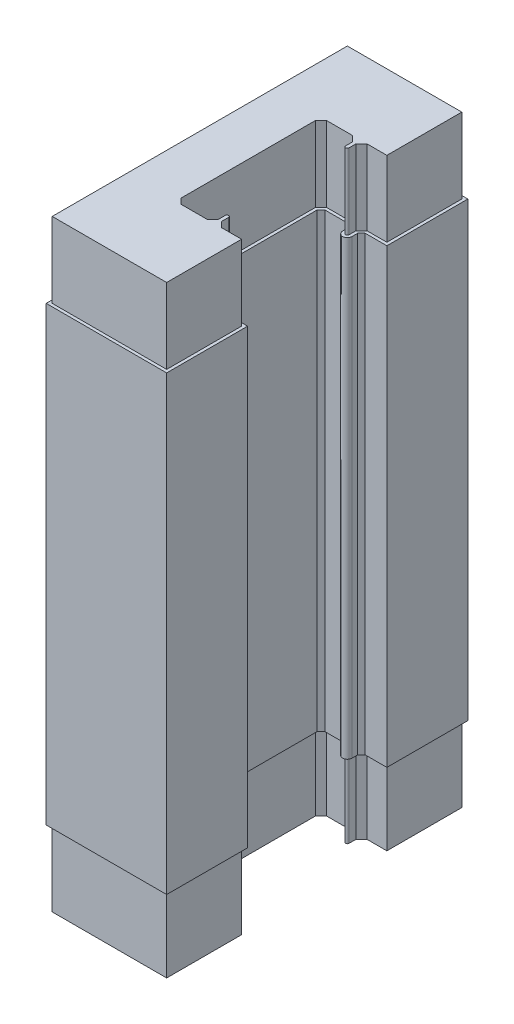
SolidWorks part; units mm, degrees
ref_plane "Front Plane" through (0, 0, 0) normal (0, 0, 1) x (1, 0, 0)
ref_plane "Top Plane" through (0, 0, 0) normal (0, 1, 0) x (1, 0, 0)
ref_plane "Right Plane" through (0, 0, 0) normal (1, 0, 0) x (0, 0, -1)
sketch "Sketch1" plane through (0, 0, 0) normal (0, 1, 0) x (1, 0, 0)
  line L1 (4.1023, -10.9252) -> (4.1023, 9.0748)
  line L4 (4.1023, -5.5502) -> (2.6648, -5.5502)
  line L6 (2.6648, -5.5502) -> (2.4148, -5.3002)
  line L7 (2.4148, -5.3002) -> (2.4148, -4.9252)
  line L8 (1.7898, -4.9252) -> (1.7898, -5.3002)
  line L9 (1.7898, -5.3002) -> (1.5398, -5.5502)
  line L10 (1.5398, -5.5502) -> (-0.0227, -5.5502)
  line L11 (-0.0227, -5.5502) -> (-0.2727, -5.3002)
  line L12 (-0.2727, -5.3002) -> (-0.2727, 3.4498)
  line L13 (2.6648, -5.5502) -> (2.4148, -5.3002)
  line L15 (-0.0227, 3.6998) -> (-0.2727, 3.4498)
  line L16 (1.5398, 3.6998) -> (-0.0227, 3.6998)
  line L17 (1.7898, 3.4498) -> (1.5398, 3.6998)
  line L18 (1.7898, 3.0748) -> (1.7898, 3.4498)
  line L19 (2.4148, 3.4498) -> (2.4148, 3.0748)
  line L20 (2.6648, 3.6998) -> (2.4148, 3.4498)
  line L21 (4.1023, 3.6998) -> (2.6648, 3.6998)
  line L22 (2.4148, -5.3002) -> (2.4148, -4.9252)
  line L23 (1.7898, -4.9252) -> (1.7898, -5.3002)
  line L24 (1.7898, -5.3002) -> (1.5398, -5.5502)
  line L25 (1.5398, -5.5502) -> (-0.0227, -5.5502)
  line L26 (-0.0227, -5.5502) -> (-0.2727, -5.3002)
  line L27 (-0.0227, 3.6998) -> (-0.2727, 3.4498)
  line L28 (1.5398, 3.6998) -> (-0.0227, 3.6998)
  line L29 (1.7898, 3.4498) -> (1.5398, 3.6998)
  line L30 (1.7898, 3.0748) -> (1.7898, 3.4498)
  line L31 (2.4148, 3.4498) -> (2.4148, 3.0748)
  line L32 (2.6648, 3.6998) -> (2.4148, 3.4498)
  line L34 (4.1023, 9.0748) -> (-3.8977, 9.0748)
  line L35 (-3.8977, 9.0748) -> (-3.8977, -10.9252)
  line L36 (-3.8977, -10.9252) -> (4.1023, -10.9252)
  line L38 (3.3835, 3.6998) -> (3.3835, -5.5502)
  arc A0 (2.4148, -4.9252) -> (2.1023, -4.6127) centre (2.1023, -4.9252) ccw
  arc A1 (2.1023, -4.6127) -> (1.7898, -4.9252) centre (2.1023, -4.9252) ccw
  arc A2 (2.1023, 2.7623) -> (1.7898, 3.0748) centre (2.1023, 3.0748) cw
  arc A3 (2.4148, 3.0748) -> (2.1023, 2.7623) centre (2.1023, 3.0748) cw
  arc A4 (2.4148, -4.9252) -> (2.1023, -4.6127) centre (2.1023, -4.9252) ccw
  arc A5 (2.1023, -4.6127) -> (1.7898, -4.9252) centre (2.1023, -4.9252) ccw
  arc A6 (2.1023, 2.7623) -> (1.7898, 3.0748) centre (2.1023, 3.0748) cw
  arc A7 (2.4148, 3.0748) -> (2.1023, 2.7623) centre (2.1023, 3.0748) cw
  point P20 (4.1023, -0.9252)
extrude "Boss-Extrude1" add sketch "Sketch1" along normal blind 40
sketch "Sketch8" plane through (0, 40, 0) normal (0, 1, 0) x (1, 0, 0)
  line L0 (2.3148, 3.0748) -> (2.3148, 3.4913)
  line L1 (2.3148, 3.4913) -> (2.6233, 3.7998)
  line L2 (2.6233, 3.7998) -> (4.0023, 3.7998)
  line L3 (4.0023, 3.7998) -> (4.0023, 8.9748)
  line L4 (4.0023, 8.9748) -> (-3.7977, 8.9748)
  line L5 (-3.7977, 8.9748) -> (-3.7977, -10.8252)
  line L6 (-3.7977, -10.8252) -> (4.0023, -10.8252)
  line L7 (4.0023, -10.8252) -> (4.0023, -5.6502)
  line L8 (4.0023, -5.6502) -> (2.6233, -5.6502)
  line L9 (2.6233, -5.6502) -> (2.3148, -5.3416)
  line L10 (2.3148, -5.3416) -> (2.3148, -4.9252)
  line L11 (1.8898, -4.9252) -> (1.8898, -5.3416)
  line L12 (1.8898, -5.3416) -> (1.5812, -5.6502)
  line L13 (1.5812, -5.6502) -> (-0.0642, -5.6502)
  line L14 (-0.0642, -5.6502) -> (-0.3727, -5.3416)
  line L15 (-0.3727, -5.3416) -> (-0.3727, 3.4913)
  line L16 (-0.3727, 3.4913) -> (-0.0642, 3.7998)
  line L17 (-0.0642, 3.7998) -> (1.5812, 3.7998)
  line L18 (1.5812, 3.7998) -> (1.8898, 3.4913)
  line L19 (1.8898, 3.4913) -> (1.8898, 3.0748)
  line L20 (2.4148, 3.0748) -> (2.4148, 3.4498)
  line L21 (2.4148, 3.4498) -> (2.6648, 3.6998)
  line L22 (2.6648, 3.6998) -> (4.1023, 3.6998)
  line L23 (4.1023, 3.6998) -> (4.1023, 9.0748)
  line L24 (4.1023, 9.0748) -> (-3.8977, 9.0748)
  line L25 (-3.8977, 9.0748) -> (-3.8977, -10.9252)
  line L26 (-3.8977, -10.9252) -> (4.1023, -10.9252)
  line L27 (4.1023, -10.9252) -> (4.1023, -5.5502)
  line L28 (4.1023, -5.5502) -> (2.6648, -5.5502)
  line L29 (2.6648, -5.5502) -> (2.4148, -5.3002)
  line L30 (2.4148, -5.3002) -> (2.4148, -4.9252)
  line L31 (1.7898, -4.9252) -> (1.7898, -5.3002)
  line L32 (1.7898, -5.3002) -> (1.5398, -5.5502)
  line L33 (1.5398, -5.5502) -> (-0.0227, -5.5502)
  line L34 (-0.0227, -5.5502) -> (-0.2727, -5.3002)
  line L35 (-0.2727, -5.3002) -> (-0.2727, 3.4498)
  line L36 (-0.2727, 3.4498) -> (-0.0227, 3.6998)
  line L37 (-0.0227, 3.6998) -> (1.5398, 3.6998)
  line L38 (1.5398, 3.6998) -> (1.7898, 3.4498)
  line L39 (1.7898, 3.4498) -> (1.7898, 3.0748)
  line L40 (2.4148, 3.0748) -> (2.4148, 3.4498)
  line L41 (2.4148, 3.4498) -> (2.6648, 3.6998)
  line L42 (2.6648, 3.6998) -> (4.1023, 3.6998)
  line L43 (4.1023, 3.6998) -> (4.1023, 9.0748)
  line L44 (4.1023, 9.0748) -> (-3.8977, 9.0748)
  line L45 (-3.8977, 9.0748) -> (-3.8977, -10.9252)
  line L46 (-3.8977, -10.9252) -> (4.1023, -10.9252)
  line L47 (4.1023, -10.9252) -> (4.1023, -5.5502)
  line L48 (4.1023, -5.5502) -> (2.6648, -5.5502)
  line L49 (2.6648, -5.5502) -> (2.4148, -5.3002)
  line L50 (2.4148, -5.3002) -> (2.4148, -4.9252)
  line L51 (1.7898, -4.9252) -> (1.7898, -5.3002)
  line L52 (1.7898, -5.3002) -> (1.5398, -5.5502)
  line L53 (1.5398, -5.5502) -> (-0.0227, -5.5502)
  line L54 (-0.0227, -5.5502) -> (-0.2727, -5.3002)
  line L55 (-0.2727, -5.3002) -> (-0.2727, 3.4498)
  line L56 (-0.2727, 3.4498) -> (-0.0227, 3.6998)
  line L57 (-0.0227, 3.6998) -> (1.5398, 3.6998)
  line L58 (1.5398, 3.6998) -> (1.7898, 3.4498)
  line L59 (1.7898, 3.4498) -> (1.7898, 3.0748)
  arc A0 (2.3148, -4.9252) -> (1.8898, -4.9252) centre (2.1023, -4.9252) ccw
  arc A1 (1.8898, 3.0748) -> (2.3148, 3.0748) centre (2.1023, 3.0748) ccw
  arc A2 (1.7898, 3.0748) -> (2.4148, 3.0748) centre (2.1023, 3.0748) ccw
  arc A3 (2.4148, -4.9252) -> (1.7898, -4.9252) centre (2.1023, -4.9252) ccw
  arc A4 (1.7898, 3.0748) -> (2.4148, 3.0748) centre (2.1023, 3.0748) ccw
  arc A5 (2.4148, -4.9252) -> (1.7898, -4.9252) centre (2.1023, -4.9252) ccw
  dimension "D1" = 0
  dimension "D2" = 0.1
extrude "Cut-Extrude6" cut sketch "Sketch8" against normal blind 5
sketch "Sketch9" plane through (0, 0, 0) normal (0, -1, 0) x (1, 0, 0)
  line L20 (1.7898, -3.0748) -> (1.7898, -3.4498)
  line L21 (1.7898, -3.4498) -> (1.5398, -3.6998)
  line L22 (1.5398, -3.6998) -> (-0.0227, -3.6998)
  line L23 (-0.0227, -3.6998) -> (-0.2727, -3.4498)
  line L24 (-0.2727, -3.4498) -> (-0.2727, 5.3002)
  line L25 (-0.2727, 5.3002) -> (-0.0227, 5.5502)
  line L26 (-0.0227, 5.5502) -> (1.5398, 5.5502)
  line L27 (1.5398, 5.5502) -> (1.7898, 5.3002)
  line L28 (1.7898, 5.3002) -> (1.7898, 4.9252)
  line L29 (2.4148, 4.9252) -> (2.4148, 5.3002)
  line L30 (2.4148, 5.3002) -> (2.6648, 5.5502)
  line L31 (2.6648, 5.5502) -> (4.1023, 5.5502)
  line L32 (4.1023, 5.5502) -> (4.1023, 10.9252)
  line L33 (4.1023, 10.9252) -> (-3.8977, 10.9252)
  line L34 (-3.8977, 10.9252) -> (-3.8977, -9.0748)
  line L35 (-3.8977, -9.0748) -> (4.1023, -9.0748)
  line L36 (4.1023, -9.0748) -> (4.1023, -3.6998)
  line L37 (4.1023, -3.6998) -> (2.6648, -3.6998)
  line L38 (2.6648, -3.6998) -> (2.4148, -3.4498)
  line L39 (2.4148, -3.4498) -> (2.4148, -3.0748)
  line L40 (1.7898, -3.0748) -> (1.7898, -3.4498)
  line L41 (1.7898, -3.4498) -> (1.5398, -3.6998)
  line L42 (1.5398, -3.6998) -> (-0.0227, -3.6998)
  line L43 (-0.0227, -3.6998) -> (-0.2727, -3.4498)
  line L44 (-0.2727, -3.4498) -> (-0.2727, 5.3002)
  line L45 (-0.2727, 5.3002) -> (-0.0227, 5.5502)
  line L46 (-0.0227, 5.5502) -> (1.5398, 5.5502)
  line L47 (1.5398, 5.5502) -> (1.7898, 5.3002)
  line L48 (1.7898, 5.3002) -> (1.7898, 4.9252)
  line L49 (2.4148, 4.9252) -> (2.4148, 5.3002)
  line L50 (2.4148, 5.3002) -> (2.6648, 5.5502)
  line L51 (2.6648, 5.5502) -> (4.1023, 5.5502)
  line L52 (4.1023, 5.5502) -> (4.1023, 10.9252)
  line L53 (4.1023, 10.9252) -> (-3.8977, 10.9252)
  line L54 (-3.8977, 10.9252) -> (-3.8977, -9.0748)
  line L55 (-3.8977, -9.0748) -> (4.1023, -9.0748)
  line L56 (4.1023, -9.0748) -> (4.1023, -3.6998)
  line L57 (4.1023, -3.6998) -> (2.6648, -3.6998)
  line L58 (2.6648, -3.6998) -> (2.4148, -3.4498)
  line L59 (2.4148, -3.4498) -> (2.4148, -3.0748)
  line L60 (1.8898, -3.0748) -> (1.8898, -3.4913)
  line L61 (2.3148, -3.4913) -> (2.3148, -3.0748)
  line L62 (2.6233, -3.7998) -> (2.3148, -3.4913)
  line L63 (4.0023, -3.7998) -> (2.6233, -3.7998)
  line L64 (4.0023, -8.9748) -> (4.0023, -3.7998)
  line L65 (-3.7977, -8.9748) -> (4.0023, -8.9748)
  line L66 (-3.7977, 10.8252) -> (-3.7977, -8.9748)
  line L67 (4.0023, 10.8252) -> (-3.7977, 10.8252)
  line L68 (4.0023, 5.6502) -> (4.0023, 10.8252)
  line L69 (2.6233, 5.6502) -> (4.0023, 5.6502)
  line L70 (2.3148, 5.3416) -> (2.6233, 5.6502)
  line L71 (2.3148, 4.9252) -> (2.3148, 5.3416)
  line L72 (1.8898, 5.3416) -> (1.8898, 4.9252)
  line L73 (1.5812, 5.6502) -> (1.8898, 5.3416)
  line L74 (-0.0642, 5.6502) -> (1.5812, 5.6502)
  line L75 (-0.3727, 5.3416) -> (-0.0642, 5.6502)
  line L76 (-0.3727, -3.4913) -> (-0.3727, 5.3416)
  line L77 (-0.0642, -3.7998) -> (-0.3727, -3.4913)
  line L78 (1.5812, -3.7998) -> (-0.0642, -3.7998)
  line L79 (1.8898, -3.4913) -> (1.5812, -3.7998)
  line L80 (1.8898, -3.0748) -> (1.8898, -3.4913)
  line L81 (2.3148, -3.4913) -> (2.3148, -3.0748)
  line L82 (2.6233, -3.7998) -> (2.3148, -3.4913)
  line L83 (4.0023, -3.7998) -> (2.6233, -3.7998)
  line L84 (4.0023, -8.9748) -> (4.0023, -3.7998)
  line L85 (-3.7977, -8.9748) -> (4.0023, -8.9748)
  line L86 (-3.7977, 10.8252) -> (-3.7977, -8.9748)
  line L87 (4.0023, 10.8252) -> (-3.7977, 10.8252)
  line L88 (4.0023, 5.6502) -> (4.0023, 10.8252)
  line L89 (2.6233, 5.6502) -> (4.0023, 5.6502)
  line L90 (2.3148, 5.3416) -> (2.6233, 5.6502)
  line L91 (2.3148, 4.9252) -> (2.3148, 5.3416)
  line L92 (1.8898, 5.3416) -> (1.8898, 4.9252)
  line L93 (1.5812, 5.6502) -> (1.8898, 5.3416)
  line L94 (-0.0642, 5.6502) -> (1.5812, 5.6502)
  line L95 (-0.3727, 5.3416) -> (-0.0642, 5.6502)
  line L96 (-0.3727, -3.4913) -> (-0.3727, 5.3416)
  line L97 (-0.0642, -3.7998) -> (-0.3727, -3.4913)
  line L98 (1.5812, -3.7998) -> (-0.0642, -3.7998)
  line L99 (1.8898, -3.4913) -> (1.5812, -3.7998)
  arc A2 (2.4148, -3.0748) -> (1.7898, -3.0748) centre (2.1023, -3.0748) ccw
  arc A3 (1.7898, 4.9252) -> (2.4148, 4.9252) centre (2.1023, 4.9252) ccw
  arc A4 (2.4148, -3.0748) -> (1.7898, -3.0748) centre (2.1023, -3.0748) ccw
  arc A5 (1.7898, 4.9252) -> (2.4148, 4.9252) centre (2.1023, 4.9252) ccw
  arc A6 (2.3148, -3.0748) -> (1.8898, -3.0748) centre (2.1023, -3.0748) ccw
  arc A7 (1.8898, 4.9252) -> (2.3148, 4.9252) centre (2.1023, 4.9252) ccw
  arc A8 (2.3148, -3.0748) -> (1.8898, -3.0748) centre (2.1023, -3.0748) ccw
  arc A9 (1.8898, 4.9252) -> (2.3148, 4.9252) centre (2.1023, 4.9252) ccw
  dimension "D1" = 0
  dimension "D2" = 0
extrude "Cut-Extrude7" cut sketch "Sketch9" against normal blind 5
sketch "Sketch10" plane through (-3.8977, 0, 0) normal (-1, 0, 0) x (0, 0, 1)
  circle A0 centre (-6.5748, 28) radius 1.5
  circle A1 centre (8.4252, 28) radius 1.5
  circle A2 centre (8.4252, 12) radius 1.5
  circle A3 centre (-6.5748, 12) radius 1.5
extrude "Cut-Extrude8" cut sketch "Sketch10" against normal blind 3
sketch "Sketch5" plane through (0, 40, 0) normal (0, 1, 0) x (1, 0, 0)
  line L20 (1.8898, 3.4913) -> (1.8898, 3.0748)
  line L21 (1.8898, 3.4913) -> (1.8898, 3.0748)
  line L22 (2.3148, 3.0748) -> (2.3148, 3.4913)
  line L23 (2.3148, 3.0748) -> (2.3148, 3.4913)
  line L24 (2.3148, 3.4913) -> (2.6233, 3.7998)
  line L25 (2.3148, 3.4913) -> (2.6233, 3.7998)
  line L26 (2.6233, 3.7998) -> (4.0023, 3.7998)
  line L27 (2.6233, 3.7998) -> (4.0023, 3.7998)
  line L28 (4.0023, 3.7998) -> (4.0023, 8.9748)
  line L29 (4.0023, 3.7998) -> (4.0023, 8.9748)
  line L30 (4.0023, 8.9748) -> (-3.7977, 8.9748)
  line L31 (4.0023, 8.9748) -> (-3.7977, 8.9748)
  line L32 (-3.7977, 8.9748) -> (-3.7977, -10.8252)
  line L33 (-3.7977, 8.9748) -> (-3.7977, -10.8252)
  line L34 (-3.7977, -10.8252) -> (4.0023, -10.8252)
  line L35 (-3.7977, -10.8252) -> (4.0023, -10.8252)
  line L36 (4.0023, -10.8252) -> (4.0023, -5.6502)
  line L37 (4.0023, -10.8252) -> (4.0023, -5.6502)
  line L38 (4.0023, -5.6502) -> (2.6233, -5.6502)
  line L39 (4.0023, -5.6502) -> (2.6233, -5.6502)
  line L60 (2.6233, -5.6502) -> (2.3148, -5.3416)
  line L61 (2.6233, -5.6502) -> (2.3148, -5.3416)
  line L62 (2.3148, -5.3416) -> (2.3148, -4.9252)
  line L63 (2.3148, -5.3416) -> (2.3148, -4.9252)
  line L64 (1.8898, -4.9252) -> (1.8898, -5.3416)
  line L65 (1.8898, -4.9252) -> (1.8898, -5.3416)
  line L66 (1.8898, -5.3416) -> (1.5812, -5.6502)
  line L67 (1.8898, -5.3416) -> (1.5812, -5.6502)
  line L68 (1.5812, -5.6502) -> (-0.0642, -5.6502)
  line L69 (1.5812, -5.6502) -> (-0.0642, -5.6502)
  line L70 (-0.0642, -5.6502) -> (-0.3727, -5.3416)
  line L71 (-0.0642, -5.6502) -> (-0.3727, -5.3416)
  line L72 (-0.3727, -5.3416) -> (-0.3727, 3.4913)
  line L73 (-0.3727, -5.3416) -> (-0.3727, 3.4913)
  line L74 (-0.3727, 3.4913) -> (-0.0642, 3.7998)
  line L75 (-0.3727, 3.4913) -> (-0.0642, 3.7998)
  line L76 (-0.0642, 3.7998) -> (1.5812, 3.7998)
  line L77 (-0.0642, 3.7998) -> (1.5812, 3.7998)
  line L78 (1.5812, 3.7998) -> (1.8898, 3.4913)
  line L79 (1.5812, 3.7998) -> (1.8898, 3.4913)
  line L80 (1.9898, 3.5327) -> (1.9898, 3.0748)
  line L81 (1.9898, 3.5327) -> (1.9898, 3.0748)
  line L82 (2.2148, 3.0748) -> (2.2148, 3.5327)
  line L83 (2.2148, 3.0748) -> (2.2148, 3.5327)
  line L84 (2.2148, 3.5327) -> (2.5819, 3.8998)
  line L85 (2.2148, 3.5327) -> (2.5819, 3.8998)
  line L86 (2.5819, 3.8998) -> (3.9023, 3.8998)
  line L87 (2.5819, 3.8998) -> (3.9023, 3.8998)
  line L88 (3.9023, 3.8998) -> (3.9023, 8.8748)
  line L89 (3.9023, 3.8998) -> (3.9023, 8.8748)
  line L90 (3.9023, 8.8748) -> (-3.6977, 8.8748)
  line L91 (3.9023, 8.8748) -> (-3.6977, 8.8748)
  line L92 (-3.6977, 8.8748) -> (-3.6977, -10.7252)
  line L93 (-3.6977, 8.8748) -> (-3.6977, -10.7252)
  line L94 (-3.6977, -10.7252) -> (3.9023, -10.7252)
  line L95 (-3.6977, -10.7252) -> (3.9023, -10.7252)
  line L96 (3.9023, -10.7252) -> (3.9023, -5.7502)
  line L97 (3.9023, -10.7252) -> (3.9023, -5.7502)
  line L98 (3.9023, -5.7502) -> (2.5819, -5.7502)
  line L99 (3.9023, -5.7502) -> (2.5819, -5.7502)
  line L120 (2.5819, -5.7502) -> (2.2148, -5.383)
  line L121 (2.5819, -5.7502) -> (2.2148, -5.383)
  line L122 (2.2148, -5.383) -> (2.2148, -4.9252)
  line L123 (2.2148, -5.383) -> (2.2148, -4.9252)
  line L124 (1.9898, -4.9252) -> (1.9898, -5.383)
  line L125 (1.9898, -4.9252) -> (1.9898, -5.383)
  line L126 (1.9898, -5.383) -> (1.6226, -5.7502)
  line L127 (1.9898, -5.383) -> (1.6226, -5.7502)
  line L128 (1.6226, -5.7502) -> (-0.1056, -5.7502)
  line L129 (1.6226, -5.7502) -> (-0.1056, -5.7502)
  line L130 (-0.1056, -5.7502) -> (-0.4727, -5.383)
  line L131 (-0.1056, -5.7502) -> (-0.4727, -5.383)
  line L132 (-0.4727, -5.383) -> (-0.4727, 3.5327)
  line L133 (-0.4727, -5.383) -> (-0.4727, 3.5327)
  line L134 (-0.4727, 3.5327) -> (-0.1056, 3.8998)
  line L135 (-0.4727, 3.5327) -> (-0.1056, 3.8998)
  line L136 (-0.1056, 3.8998) -> (1.6226, 3.8998)
  line L137 (-0.1056, 3.8998) -> (1.6226, 3.8998)
  line L138 (1.6226, 3.8998) -> (1.9898, 3.5327)
  line L139 (1.6226, 3.8998) -> (1.9898, 3.5327)
  arc A2 (1.8898, 3.0748) -> (2.3148, 3.0748) centre (2.1023, 3.0748) ccw
  arc A3 (1.8898, 3.0748) -> (2.3148, 3.0748) centre (2.1023, 3.0748) ccw
  arc A6 (2.3148, -4.9252) -> (1.8898, -4.9252) centre (2.1023, -4.9252) ccw
  arc A7 (2.3148, -4.9252) -> (1.8898, -4.9252) centre (2.1023, -4.9252) ccw
  arc A8 (1.9898, 3.0748) -> (2.2148, 3.0748) centre (2.1023, 3.0748) ccw
  arc A9 (1.9898, 3.0748) -> (2.2148, 3.0748) centre (2.1023, 3.0748) ccw
  arc A12 (2.2148, -4.9252) -> (1.9898, -4.9252) centre (2.1023, -4.9252) ccw
  arc A13 (2.2148, -4.9252) -> (1.9898, -4.9252) centre (2.1023, -4.9252) ccw
  dimension "D1" = 0
  dimension "D2" = 0.1
extrude "Cut-Extrude4" cut sketch "Sketch5" against normal blind 5
sketch "Sketch3" plane through (0, 0, 0) normal (0, -1, 0) x (1, 0, 0)
  line L20 (1.6226, -3.8998) -> (-0.1056, -3.8998)
  line L22 (1.6226, -3.8998) -> (-0.1056, -3.8998)
  line L24 (1.9898, -3.5327) -> (1.6226, -3.8998)
  line L26 (1.9898, -3.5327) -> (1.6226, -3.8998)
  line L28 (1.9898, -3.0748) -> (1.9898, -3.5327)
  line L30 (1.9898, -3.0748) -> (1.9898, -3.5327)
  line L32 (2.2148, -3.5327) -> (2.2148, -3.0748)
  line L34 (2.2148, -3.5327) -> (2.2148, -3.0748)
  line L36 (2.5819, -3.8998) -> (2.2148, -3.5327)
  line L38 (2.5819, -3.8998) -> (2.2148, -3.5327)
  line L60 (1.8898, -3.4913) -> (1.5812, -3.7998)
  line L61 (1.8898, -3.4913) -> (1.5812, -3.7998)
  line L62 (1.5812, -3.7998) -> (-0.0642, -3.7998)
  line L63 (1.5812, -3.7998) -> (-0.0642, -3.7998)
  line L64 (-0.0642, -3.7998) -> (-0.3727, -3.4913)
  line L65 (-0.0642, -3.7998) -> (-0.3727, -3.4913)
  line L66 (-0.3727, -3.4913) -> (-0.3727, 5.3416)
  line L67 (-0.3727, -3.4913) -> (-0.3727, 5.3416)
  line L68 (-0.3727, 5.3416) -> (-0.0642, 5.6502)
  line L69 (-0.3727, 5.3416) -> (-0.0642, 5.6502)
  line L70 (-0.0642, 5.6502) -> (1.5812, 5.6502)
  line L71 (-0.0642, 5.6502) -> (1.5812, 5.6502)
  line L72 (1.5812, 5.6502) -> (1.8898, 5.3416)
  line L73 (1.5812, 5.6502) -> (1.8898, 5.3416)
  line L75 (1.8898, 5.3416) -> (1.8898, 4.9252)
  line L76 (1.8898, 5.3416) -> (1.8898, 4.9252)
  line L77 (2.3148, 4.9252) -> (2.3148, 5.3416)
  line L78 (2.3148, 4.9252) -> (2.3148, 5.3416)
  line L79 (2.3148, 5.3416) -> (2.6233, 5.6502)
  line L100 (3.9023, -3.8998) -> (2.5819, -3.8998)
  line L102 (3.9023, -3.8998) -> (2.5819, -3.8998)
  line L104 (3.9023, -8.8748) -> (3.9023, -3.8998)
  line L106 (3.9023, -8.8748) -> (3.9023, -3.8998)
  line L108 (-3.6977, -8.8748) -> (3.9023, -8.8748)
  line L110 (-3.6977, -8.8748) -> (3.9023, -8.8748)
  line L112 (-3.6977, 10.7252) -> (-3.6977, -8.8748)
  line L114 (-3.6977, 10.7252) -> (-3.6977, -8.8748)
  line L116 (3.9023, 10.7252) -> (-3.6977, 10.7252)
  line L118 (3.9023, 10.7252) -> (-3.6977, 10.7252)
  line L121 (2.3148, 5.3416) -> (2.6233, 5.6502)
  line L123 (3.9023, 5.7502) -> (3.9023, 10.7252)
  line L124 (3.9023, 5.7502) -> (3.9023, 10.7252)
  line L125 (2.5819, 5.7502) -> (3.9023, 5.7502)
  line L126 (2.5819, 5.7502) -> (3.9023, 5.7502)
  line L127 (2.2148, 5.383) -> (2.5819, 5.7502)
  line L128 (2.2148, 5.383) -> (2.5819, 5.7502)
  line L129 (2.2148, 4.9252) -> (2.2148, 5.383)
  line L130 (2.2148, 4.9252) -> (2.2148, 5.383)
  line L131 (1.9898, 5.383) -> (1.9898, 4.9252)
  line L132 (1.9898, 5.383) -> (1.9898, 4.9252)
  line L133 (1.6226, 5.7502) -> (1.9898, 5.383)
  line L134 (1.6226, 5.7502) -> (1.9898, 5.383)
  line L135 (-0.1056, 5.7502) -> (1.6226, 5.7502)
  line L136 (-0.1056, 5.7502) -> (1.6226, 5.7502)
  line L137 (-0.4727, 5.383) -> (-0.1056, 5.7502)
  line L138 (-0.4727, 5.383) -> (-0.1056, 5.7502)
  line L139 (-0.4727, -3.5327) -> (-0.4727, 5.383)
  line L140 (-0.4727, -3.5327) -> (-0.4727, 5.383)
  line L141 (-0.1056, -3.8998) -> (-0.4727, -3.5327)
  line L142 (-0.1056, -3.8998) -> (-0.4727, -3.5327)
  line L143 (2.6233, 5.6502) -> (4.0023, 5.6502)
  line L144 (2.6233, 5.6502) -> (4.0023, 5.6502)
  line L145 (4.0023, 5.6502) -> (4.0023, 10.8252)
  line L146 (4.0023, 5.6502) -> (4.0023, 10.8252)
  line L147 (4.0023, 10.8252) -> (-3.7977, 10.8252)
  line L148 (4.0023, 10.8252) -> (-3.7977, 10.8252)
  line L149 (-3.7977, 10.8252) -> (-3.7977, -8.9748)
  line L150 (-3.7977, 10.8252) -> (-3.7977, -8.9748)
  line L151 (-3.7977, -8.9748) -> (4.0023, -8.9748)
  line L152 (-3.7977, -8.9748) -> (4.0023, -8.9748)
  line L153 (4.0023, -8.9748) -> (4.0023, -3.7998)
  line L154 (4.0023, -8.9748) -> (4.0023, -3.7998)
  line L155 (4.0023, -3.7998) -> (2.6233, -3.7998)
  line L156 (4.0023, -3.7998) -> (2.6233, -3.7998)
  line L157 (2.6233, -3.7998) -> (2.3148, -3.4913)
  line L158 (2.6233, -3.7998) -> (2.3148, -3.4913)
  line L159 (2.3148, -3.4913) -> (2.3148, -3.0748)
  line L160 (2.3148, -3.4913) -> (2.3148, -3.0748)
  line L161 (1.8898, -3.0748) -> (1.8898, -3.4913)
  line L162 (1.8898, -3.0748) -> (1.8898, -3.4913)
  arc A2 (2.2148, -3.0748) -> (1.9898, -3.0748) centre (2.1023, -3.0748) ccw
  arc A6 (1.8898, 4.9252) -> (2.3148, 4.9252) centre (2.1023, 4.9252) ccw
  arc A7 (1.8898, 4.9252) -> (2.3148, 4.9252) centre (2.1023, 4.9252) ccw
  arc A10 (2.2148, -3.0748) -> (1.9898, -3.0748) centre (2.1023, -3.0748) ccw
  arc A12 (1.9898, 4.9252) -> (2.2148, 4.9252) centre (2.1023, 4.9252) ccw
  arc A13 (1.9898, 4.9252) -> (2.2148, 4.9252) centre (2.1023, 4.9252) ccw
  arc A14 (2.3148, -3.0748) -> (1.8898, -3.0748) centre (2.1023, -3.0748) ccw
  arc A15 (2.3148, -3.0748) -> (1.8898, -3.0748) centre (2.1023, -3.0748) ccw
  dimension "D1" = 0
  dimension "D2" = 0
sketch "Sketch6" plane through (0, 0, 0) normal (0, -1, 0) x (1, 0, 0)
  line L20 (1.8898, -3.4913) -> (1.5812, -3.7998)
  line L21 (1.8898, -3.4913) -> (1.5812, -3.7998)
  line L22 (1.5812, -3.7998) -> (-0.0642, -3.7998)
  line L23 (1.5812, -3.7998) -> (-0.0642, -3.7998)
  line L24 (-0.0642, -3.7998) -> (-0.3727, -3.4913)
  line L25 (-0.0642, -3.7998) -> (-0.3727, -3.4913)
  line L26 (-0.3727, -3.4913) -> (-0.3727, 5.3416)
  line L27 (-0.3727, -3.4913) -> (-0.3727, 5.3416)
  line L28 (-0.3727, 5.3416) -> (-0.0642, 5.6502)
  line L29 (-0.3727, 5.3416) -> (-0.0642, 5.6502)
  line L30 (-0.0642, 5.6502) -> (1.5812, 5.6502)
  line L31 (-0.0642, 5.6502) -> (1.5812, 5.6502)
  line L32 (1.5812, 5.6502) -> (1.8898, 5.3416)
  line L33 (1.5812, 5.6502) -> (1.8898, 5.3416)
  line L34 (1.8898, 5.3416) -> (1.8898, 4.9252)
  line L35 (1.8898, 5.3416) -> (1.8898, 4.9252)
  line L36 (2.3148, 4.9252) -> (2.3148, 5.3416)
  line L37 (2.3148, 4.9252) -> (2.3148, 5.3416)
  line L38 (2.3148, 5.3416) -> (2.6233, 5.6502)
  line L39 (2.3148, 5.3416) -> (2.6233, 5.6502)
  line L60 (1.6226, -3.8998) -> (-0.1056, -3.8998)
  line L61 (1.6226, -3.8998) -> (-0.1056, -3.8998)
  line L62 (1.9898, -3.5327) -> (1.6226, -3.8998)
  line L63 (1.9898, -3.5327) -> (1.6226, -3.8998)
  line L64 (1.9898, -3.0748) -> (1.9898, -3.5327)
  line L65 (1.9898, -3.0748) -> (1.9898, -3.5327)
  line L66 (2.2148, -3.5327) -> (2.2148, -3.0748)
  line L67 (2.2148, -3.5327) -> (2.2148, -3.0748)
  line L68 (2.5819, -3.8998) -> (2.2148, -3.5327)
  line L69 (2.5819, -3.8998) -> (2.2148, -3.5327)
  line L70 (3.9023, -3.8998) -> (2.5819, -3.8998)
  line L71 (3.9023, -3.8998) -> (2.5819, -3.8998)
  line L72 (3.9023, -8.8748) -> (3.9023, -3.8998)
  line L73 (3.9023, -8.8748) -> (3.9023, -3.8998)
  line L74 (-3.6977, -8.8748) -> (3.9023, -8.8748)
  line L75 (-3.6977, -8.8748) -> (3.9023, -8.8748)
  line L76 (-3.6977, 10.7252) -> (-3.6977, -8.8748)
  line L77 (-3.6977, 10.7252) -> (-3.6977, -8.8748)
  line L78 (3.9023, 10.7252) -> (-3.6977, 10.7252)
  line L79 (3.9023, 10.7252) -> (-3.6977, 10.7252)
  line L100 (2.6233, 5.6502) -> (4.0023, 5.6502)
  line L101 (2.6233, 5.6502) -> (4.0023, 5.6502)
  line L102 (4.0023, 5.6502) -> (4.0023, 10.8252)
  line L103 (4.0023, 5.6502) -> (4.0023, 10.8252)
  line L104 (4.0023, 10.8252) -> (-3.7977, 10.8252)
  line L105 (4.0023, 10.8252) -> (-3.7977, 10.8252)
  line L106 (-3.7977, 10.8252) -> (-3.7977, -8.9748)
  line L107 (-3.7977, 10.8252) -> (-3.7977, -8.9748)
  line L108 (-3.7977, -8.9748) -> (4.0023, -8.9748)
  line L109 (-3.7977, -8.9748) -> (4.0023, -8.9748)
  line L110 (4.0023, -8.9748) -> (4.0023, -3.7998)
  line L111 (4.0023, -8.9748) -> (4.0023, -3.7998)
  line L112 (4.0023, -3.7998) -> (2.6233, -3.7998)
  line L113 (4.0023, -3.7998) -> (2.6233, -3.7998)
  line L114 (2.6233, -3.7998) -> (2.3148, -3.4913)
  line L115 (2.6233, -3.7998) -> (2.3148, -3.4913)
  line L116 (2.3148, -3.4913) -> (2.3148, -3.0748)
  line L117 (2.3148, -3.4913) -> (2.3148, -3.0748)
  line L118 (1.8898, -3.0748) -> (1.8898, -3.4913)
  line L119 (1.8898, -3.0748) -> (1.8898, -3.4913)
  line L120 (3.9023, 5.7502) -> (3.9023, 10.7252)
  line L121 (3.9023, 5.7502) -> (3.9023, 10.7252)
  line L122 (2.5819, 5.7502) -> (3.9023, 5.7502)
  line L123 (2.5819, 5.7502) -> (3.9023, 5.7502)
  line L124 (2.2148, 5.383) -> (2.5819, 5.7502)
  line L125 (2.2148, 5.383) -> (2.5819, 5.7502)
  line L126 (2.2148, 4.9252) -> (2.2148, 5.383)
  line L127 (2.2148, 4.9252) -> (2.2148, 5.383)
  line L128 (1.9898, 5.383) -> (1.9898, 4.9252)
  line L129 (1.9898, 5.383) -> (1.9898, 4.9252)
  line L130 (1.6226, 5.7502) -> (1.9898, 5.383)
  line L131 (1.6226, 5.7502) -> (1.9898, 5.383)
  line L132 (-0.1056, 5.7502) -> (1.6226, 5.7502)
  line L133 (-0.1056, 5.7502) -> (1.6226, 5.7502)
  line L134 (-0.4727, 5.383) -> (-0.1056, 5.7502)
  line L135 (-0.4727, 5.383) -> (-0.1056, 5.7502)
  line L136 (-0.4727, -3.5327) -> (-0.4727, 5.383)
  line L137 (-0.4727, -3.5327) -> (-0.4727, 5.383)
  line L138 (-0.1056, -3.8998) -> (-0.4727, -3.5327)
  line L139 (-0.1056, -3.8998) -> (-0.4727, -3.5327)
  arc A2 (1.8898, 4.9252) -> (2.3148, 4.9252) centre (2.1023, 4.9252) ccw
  arc A3 (1.8898, 4.9252) -> (2.3148, 4.9252) centre (2.1023, 4.9252) ccw
  arc A6 (2.2148, -3.0748) -> (1.9898, -3.0748) centre (2.1023, -3.0748) ccw
  arc A7 (2.2148, -3.0748) -> (1.9898, -3.0748) centre (2.1023, -3.0748) ccw
  arc A10 (2.3148, -3.0748) -> (1.8898, -3.0748) centre (2.1023, -3.0748) ccw
  arc A11 (2.3148, -3.0748) -> (1.8898, -3.0748) centre (2.1023, -3.0748) ccw
  arc A12 (1.9898, 4.9252) -> (2.2148, 4.9252) centre (2.1023, 4.9252) ccw
  arc A13 (1.9898, 4.9252) -> (2.2148, 4.9252) centre (2.1023, 4.9252) ccw
  dimension "D1" = 0
  dimension "D2" = 0
extrude "Cut-Extrude5" cut sketch "Sketch6" against normal blind 5
sketch "Sketch7" plane through (-3.8977, 0, 0) normal (-1, 0, 0) x (0, 0, 1)
  line L0 (-9.0748, 20) -> (10.9252, 20)
  line L1 (-9.0748, 35) -> (-9.0748, 5) construction
  line L2 (10.9252, 35) -> (10.9252, 5) construction
  line L4 (-6.5748, 28) -> (8.4252, 28)
  line L5 (-6.5748, 28) -> (-6.5748, 12)
  line L6 (-6.5748, 12) -> (8.4252, 12)
  line L7 (8.4252, 28) -> (8.4252, 12)
  line L8 (-6.5748, 28) -> (8.4252, 12) construction
  line L9 (-6.5748, 12) -> (8.4252, 28) construction
  point P6 (0.9252, 20)
